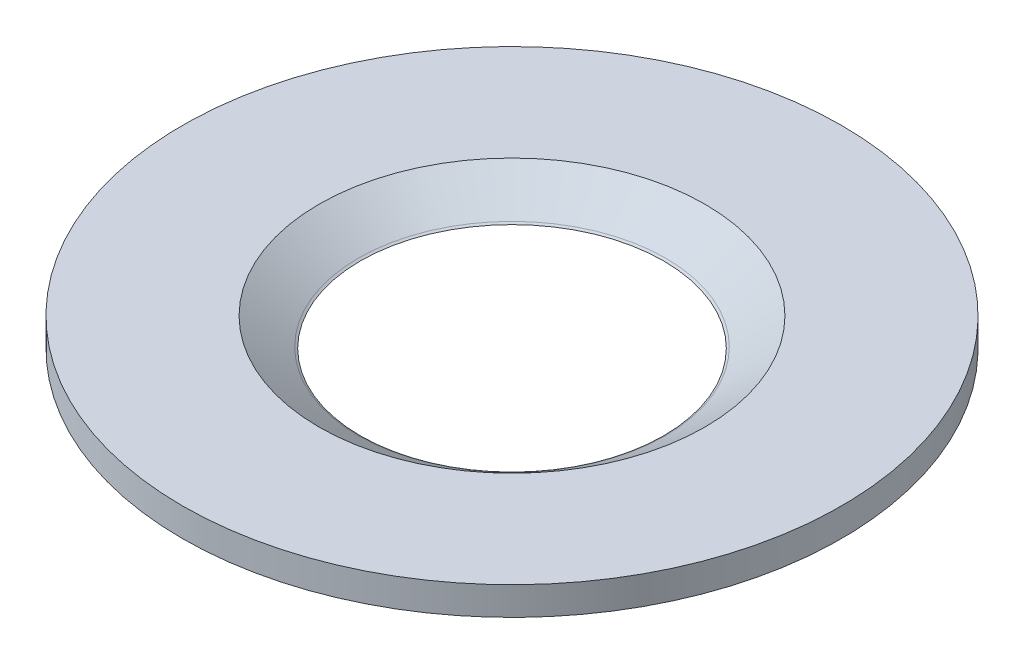
SolidWorks part; units mm, degrees
ref_plane "Front Plane" through (0, 0, 0) normal (0, 0, 1) x (1, 0, 0)
ref_plane "Top Plane" through (0, 0, 0) normal (0, 1, 0) x (1, 0, 0)
ref_plane "Right Plane" through (0, 0, 0) normal (1, 0, 0) x (0, 0, -1)
sketch "Sk_washer_section" plane through (0, 0, 0) normal (0, 0, 1) x (1, 0, 0)
  line L0 (10.1854, 62.5856) -> (22.1488, 62.5856)
  line L1 (22.1488, 62.5856) -> (22.1488, 64.4906)
  line L2 (22.1488, 64.4906) -> (12.9718, 64.4906)
  line L3 (12.9718, 64.4906) -> (10.3276, 62.6745)
  line L4 (0, -25.4) -> (0, 76.2) construction
  arc A0 (10.3276, 62.6745) -> (10.1854, 62.5856) centre (9.4091, 63.9859) cw
revolve "Rev_washer" add sketch "Sk_washer_section" angle 360 about L4
